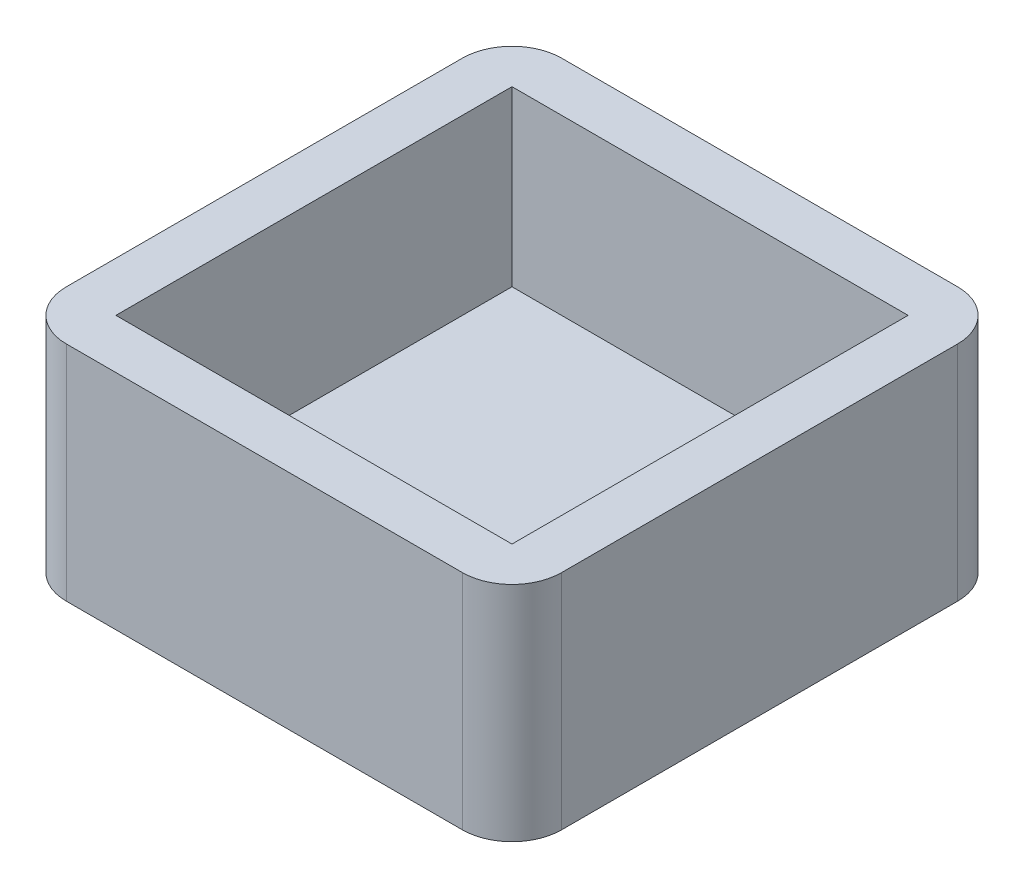
SolidWorks part; units mm, degrees
ref_plane "Front Plane" through (0, 0, 0) normal (0, 0, 1) x (1, 0, 0)
ref_plane "Top Plane" through (0, 0, 0) normal (0, 1, 0) x (1, 0, 0)
ref_plane "Right Plane" through (0, 0, 0) normal (1, 0, 0) x (0, 0, -1)
sketch "Sketch2" plane through (0, 0, 0) normal (0, 0, 1) x (1, 0, 0)
  line L0 (0, 0) -> (-75, 0)
  line L1 (-80, 5) -> (-80, 25)
  line L2 (-77, 28) -> (-63, 28)
  line L3 (-60, 25) -> (-60, 8)
  line L4 (-55, 3) -> (0, 3)
  line L5 (0, 3) -> (0, 0)
  arc A0 (-60, 8) -> (-55, 3) centre (-55, 8) ccw
  arc A1 (-75, 0) -> (-80, 5) centre (-75, 5) cw
  arc A2 (-63, 28) -> (-60, 25) centre (-63, 25) cw
  arc A3 (-80, 25) -> (-77, 28) centre (-77, 25) cw
  point P9 (-60, 3)
  point P12 (-80, 0)
  point P15 (-60, 28)
  dimension "D5" = 5
  dimension "D6" = 3
  dimension "D1" = 80
  dimension "D2" = 25
  dimension "D3" = 60
  dimension "D4" = 3
sketch "Sketch3" plane through (0, 0, 0) normal (0, 1, 0) x (1, 0, 0)
  line L1 (0, 0) -> (100, 0)
  line L2 (0, 0) -> (0, 100)
  line L3 (0, 100) -> (100, 100)
  line L4 (100, 0) -> (100, 100)
  dimension "D1" = 100
  dimension "D2" = 100
extrude "Boss-Extrude1" add sketch "Sketch3" along normal blind 10
sketch "Sketch4" plane through (0, 10, 0) normal (0, 1, 0) x (1, 0, 0)
  line L10 (100, 0) -> (100, 100) construction
  line L11 (0, 0) -> (100, 0) construction
  line L12 (0, 100) -> (0, 0) construction
  line L13 (100, 100) -> (0, 100) construction
  line L14 (90, 10) -> (90, 90)
  line L15 (10, 10) -> (90, 10)
  line L16 (10, 90) -> (10, 10)
  line L17 (90, 90) -> (10, 90)
  line L18 (90, 10) -> (90, 90)
  line L19 (10, 10) -> (90, 10)
  line L20 (10, 90) -> (10, 10)
  line L21 (90, 90) -> (10, 90)
  line L22 (100, 0) -> (100, 100)
  line L23 (0, 0) -> (100, 0)
  line L24 (0, 100) -> (0, 0)
  line L25 (100, 100) -> (0, 100)
  dimension "D1" = 10
extrude "Boss-Extrude2" add sketch "Sketch4" along normal blind 35
fillet "Fillet1" radius 10 4 edges at (0, 22.5, -100) (100, 22.5, -100) (100, 22.5, 0) (0, 22.5, 0)
